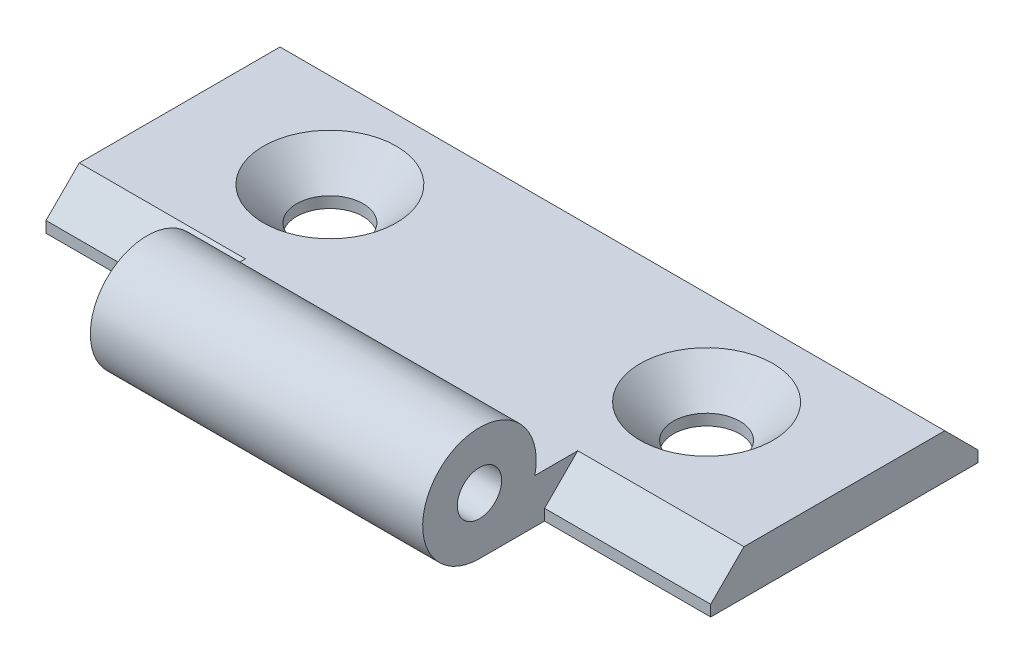
SolidWorks part; units mm, degrees
ref_plane "前视基准面" through (0, 0, 0) normal (0, 0, 1) x (1, 0, 0)
ref_plane "上视基准面" through (0, 0, 0) normal (0, 1, 0) x (1, 0, 0)
ref_plane "右视基准面" through (0, 0, 0) normal (1, 0, 0) x (0, 0, -1)
sketch "草图1" plane through (0, 0, 0) normal (1, 0, 0) x (0, 0, -1)
  line L1 (0, 0) -> (30, 0)
  line L3 (5, 4) -> (30, 4)
  line L4 (30, 0) -> (30, 4)
  circle A0 centre (0, 5.125) radius 2
  arc A1 (5, 4) -> (0, 0) centre (0, 5.125) ccw
  dimension "D4" = 4
  dimension "D1" = 25
  dimension "D2" = 30
  dimension "D3" = 4
extrude "凸台-拉伸1" add sketch "草图1" along normal mid plane 60
sketch "草图2" plane through (0, 0, 0) normal (0, 1, 0) x (1, 0, 0)
  line L5 (0, 0) -> (0, 22.9721) construction
  line L6 (15, -5.125) -> (15, 5.875)
  line L7 (-30, -5.125) -> (-15, -5.125)
  line L8 (-30, -5.125) -> (-30, 5.875)
  line L9 (-30, 5.875) -> (-15, 5.875)
  line L10 (-15, -5.125) -> (-15, 5.875)
  line L11 (30, 5.875) -> (15, 5.875)
  line L12 (30, -5.125) -> (30, 5.875)
  line L13 (30, -5.125) -> (15, -5.125)
  circle A0 centre (-17, 18.5) radius 3
  circle A1 centre (17, 18.5) radius 3
  dimension "D2" = 6
  dimension "D1" = 11
  dimension "D3" = 34
  dimension "D4" = 15
  dimension "D5" = 18.5
extrude "切除-拉伸1" cut sketch "草图2" along normal through all
chamfer "倒角1" distance 3 angle 45 5 edges at (-22.5, 4, -5.875) (-17, 4, -21.5) (17, 4, -21.5) (0, 4, -30) (22.5, 4, -5.875)
